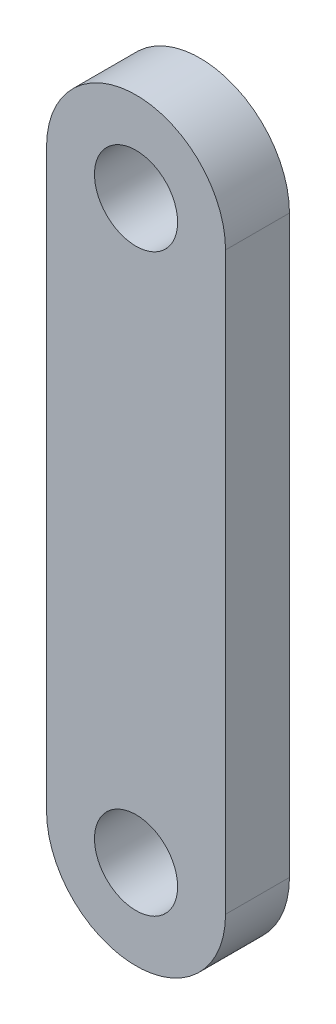
SolidWorks part; units mm, degrees
ref_plane "Front Plane" through (0, 0, 0) normal (0, 0, 1) x (1, 0, 0)
ref_plane "Top Plane" through (0, 0, 0) normal (0, 1, 0) x (1, 0, 0)
ref_plane "Right Plane" through (0, 0, 0) normal (1, 0, 0) x (0, 0, -1)
sketch "Sketch1" plane through (0, 0, 0) normal (0, 0, 1) x (1, 0, 0)
  line L0 (0, -39.0716) -> (0, 5.9284) construction
  line L1 (-7, -39.0716) -> (-7, 5.9284)
  line L2 (7, -39.0716) -> (7, 5.9284)
  arc A0 (-7, -39.0716) -> (7, -39.0716) centre (0, -39.0716) ccw
  arc A1 (7, 5.9284) -> (-7, 5.9284) centre (0, 5.9284) ccw
  point P3 (0, -16.5716)
extrude "Boss-Extrude1" add sketch "Sketch1" along normal blind 5
sketch "Sketch2" plane through (0, 0, 5) normal (0, 0, 1) x (1, 0, 0)
  circle A0 centre (0, 5.9284) radius 3.25
  circle A1 centre (0, -39.0716) radius 3.25
  arc A2 (-7, -39.0716) -> (7, -39.0716) centre (0, -39.0716) ccw construction
  point P7 (0, -46.0716)
  dimension "D1" = 6.5
  dimension "D2" = 6.5
  dimension "D3" = 45
  dimension "D4" = 7
extrude "Cut-Extrude1" cut sketch "Sketch2" against normal through all contours A1 | A0
